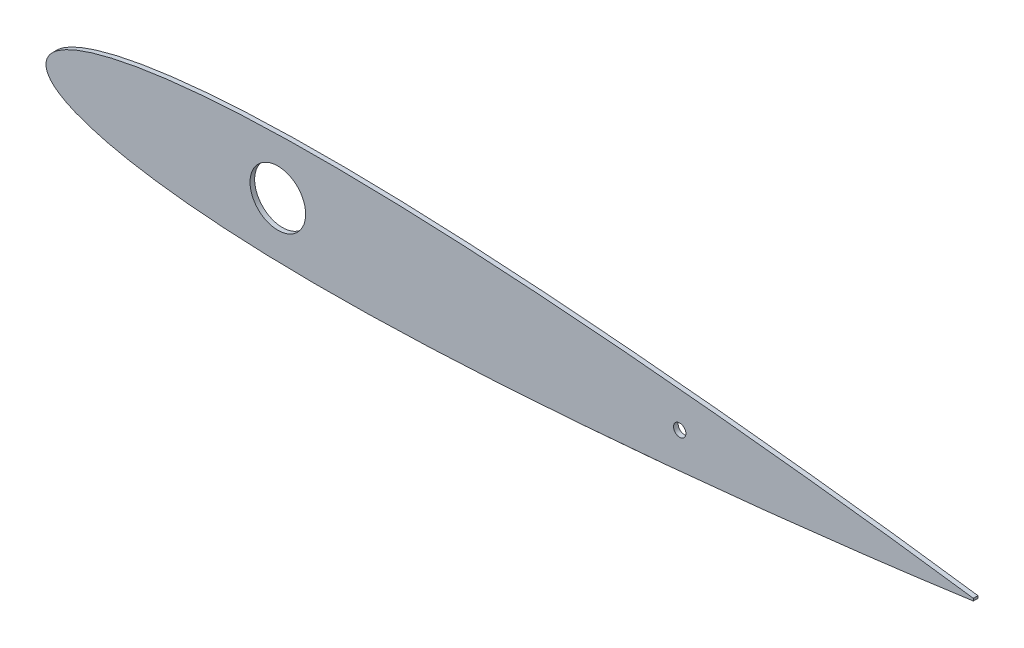
SolidWorks part; units mm, degrees
material "Oak"
ref_plane "Front Plane" through (0, 0, 0) normal (0, 0, 1) x (1, 0, 0)
ref_plane "Top Plane" through (0, 0, 0) normal (0, 1, 0) x (1, 0, 0)
ref_plane "Right Plane" through (0, 0, 0) normal (1, 0, 0) x (0, 0, -1)
sketch "Sketch5" plane through (0, 0, 0) normal (0, 0, 1) x (1, 0, 0)
  line L1 (300, 0.378) -> (300, -0.378)
  spline S1 degree 3 poles (300, 0.378) (299.2704, 0.4794) (297.2347, 0.7625) (293.6597, 1.2577) (289.1124, 1.8742) (284.0808, 2.5445) (278.752, 3.2381) (273.2659, 3.9349) (267.706, 4.629) (262.1146, 5.3131) (256.5083, 5.9822) (250.8917, 6.638) (245.2696, 7.2818) (239.6473, 7.9122) (234.0251, 8.527) (228.3991, 9.1262) (222.7683, 9.7131) (217.1359, 10.2875) (211.5054, 10.8469) (205.8776, 11.3916) (200.2515, 11.9209) (194.6264, 12.4346) (189.0028, 12.9319) (183.3815, 13.4131) (177.7632, 13.8764) (172.1483, 14.3212) (166.5375, 14.7478) (160.9317, 15.1542) (155.3317, 15.5391) (149.7375, 15.9026) (144.1487, 16.2418) (138.5657, 16.5574) (132.9909, 16.8474) (127.4274, 17.1102) (121.8776, 17.3439) (116.3408, 17.5453) (110.8155, 17.7127) (105.3013, 17.8445) (99.8006, 17.9401) (94.3174, 17.9966) (88.8558, 18.0101) (83.4186, 17.9792) (78.0085, 17.8992) (72.6285, 17.767) (67.2827, 17.5794) (61.9774, 17.3315) (56.7207, 17.021) (51.5252, 16.641) (46.4082, 16.1902) (41.3942, 15.6617) (36.5157, 15.054) (31.819, 14.3656) (27.3662, 13.6035) (23.2352, 12.7826) (19.5026, 11.9203) (16.2183, 11.0446) (13.3892, 10.1751) (10.9849, 9.3335) (8.9616, 8.5221) (7.2673, 7.747) (5.8461, 7.0106) (4.6477, 6.3006) (3.6282, 5.6065) (2.7519, 4.9266) (2.0063, 4.2499) (1.3906, 3.5703) (0.901, 2.8909) (0.5293, 2.2202) (0.2605, 1.5665) (0.0857, 0.931) (-0.0035, 0.309) (-0.0035, -0.309) (0.0857, -0.931) (0.2605, -1.5665) (0.5293, -2.2202) (0.901, -2.8909) (1.3906, -3.5703) (2.0063, -4.2499) (2.7519, -4.9266) (3.6282, -5.6065) (4.6477, -6.3006) (5.8461, -7.0106) (7.2673, -7.747) (8.9616, -8.5221) (10.9849, -9.3335) (13.3892, -10.1751) (16.2183, -11.0446) (19.5026, -11.9203) (23.2352, -12.7826) (27.3661, -13.6036) (31.8191, -14.3651) (36.5156, -15.0541) (41.3942, -15.6616) (46.4082, -16.1902) (51.5252, -16.641) (56.7207, -17.021) (61.9774, -17.3315) (67.2827, -17.5794) (72.6285, -17.767) (78.0085, -17.8992) (83.4186, -17.9792) (88.8558, -18.0101) (94.3174, -17.9966) (99.8006, -17.9401) (105.3013, -17.8445) (110.8155, -17.7127) (116.3408, -17.5453) (121.8776, -17.3439) (127.4274, -17.1102) (132.9909, -16.8474) (138.5657, -16.5574) (144.1487, -16.2418) (149.7375, -15.9026) (155.3317, -15.5391) (160.9317, -15.1542) (166.5375, -14.7478) (172.1483, -14.3212) (177.7632, -13.8764) (183.3815, -13.4131) (189.0028, -12.9319) (194.6264, -12.4346) (200.2515, -11.9209) (205.8776, -11.3916) (211.5054, -10.8469) (217.1359, -10.2875) (222.7683, -9.7131) (228.3991, -9.1262) (234.0251, -8.527) (239.6473, -7.9122) (245.2696, -7.2818) (250.8917, -6.638) (256.5083, -5.9822) (262.1146, -5.3131) (267.706, -4.629) (273.2659, -3.9349) (278.752, -3.2381) (284.0808, -2.5445) (289.1124, -1.8742) (293.6597, -1.2577) (297.2347, -0.7625) (299.2704, -0.4794) (300, -0.378) knots 0 0 0 0 0.003612 0.010079 0.017699 0.026115 0.034971 0.04405 0.053234 0.062448 0.071674 0.080921 0.090178 0.099424 0.108664 0.117912 0.12717 0.136427 0.145675 0.154916 0.164153 0.173387 0.182616 0.191838 0.201053 0.21026 0.219459 0.228647 0.237822 0.246985 0.256137 0.265279 0.274407 0.283512 0.292592 0.301646 0.310682 0.319699 0.328695 0.33766 0.346589 0.355477 0.364323 0.373122 0.381868 0.390553 0.399166 0.40769 0.416098 0.424355 0.432412 0.440205 0.447631 0.454564 0.460855 0.466413 0.471229 0.475366 0.478901 0.481915 0.484499 0.486747 0.488741 0.490543 0.492182 0.493673 0.495032 0.496279 0.497425 0.49849 0.499503 0.500497 0.50151 0.502575 0.503721 0.504968 0.506327 0.507818 0.509457 0.511259 0.513253 0.515501 0.518085 0.521099 0.524634 0.528771 0.533587 0.539145 0.545436 0.55237 0.559795 0.567588 0.575645 0.583902 0.59231 0.600834 0.609447 0.618132 0.626878 0.635677 0.644523 0.653411 0.66234 0.671305 0.680301 0.689318 0.698354 0.707408 0.716488 0.725593 0.734721 0.743863 0.753015 0.762178 0.771353 0.780541 0.78974 0.798947 0.808162 0.817384 0.826613 0.835847 0.845084 0.854325 0.863573 0.87283 0.882088 0.891336 0.900576 0.909822 0.919079 0.928326 0.937552 0.946766 0.95595 0.965029 0.973885 0.982301 0.989921 0.996388 1 1 1 1
  dimension "Tail chord" = 300
extrude "Boss-Extrude1" add sketch "Sketch5" along normal blind 1.5
ref_plane "Plane1" through (0, 0, 1.5) normal (0, 0, 1) x (1, 0, 0)
sketch "Sketch7" plane through (0, 0, 1.5) normal (0, 0, 1) x (1, 0, 0)
  circle A0 centre (75, 0) radius 9
  circle A1 centre (205, 0) radius 2
  dimension "D1" = 18
  dimension "D3" = 4
  dimension "Tail chord qtr" = 75
  dimension "Small hole" = 130
extrude "Cut-Extrude7" cut sketch "Sketch7" against normal through all
curve "Curve6"
  spline degree 3 poles (298.242, -0.1932, 0) (300.4407, 0, 0) (298.242, 0.1932, 0) (296.4349, 0.5367, 0) (292.0253, 1.0976, 0) (286.5771, 1.8592, 0) (279.4156, 2.8001, 0) (270.9173, 3.8949, 0) (261.066, 5.1159, 0) (250.0071, 6.4339, 0) (237.8495, 7.8187, 0) (224.7304, 9.2395, 0) (210.7923, 10.6647, 0) (196.1883, 12.0613, 0) (181.0783, 13.3946, 0) (165.6277, 14.6278, 0) (150.0058, 15.7225, 0) (134.3834, 16.6392, 0) (118.9317, 17.3387, 0) (103.8195, 17.7845, 0) (89.2123, 17.9443, 0) (75.2698, 17.7935, 0) (62.1444, 17.3161, 0) (49.9793, 16.5075, 0) (38.907, 15.374, 0) (29.0471, 13.9333, 0) (20.5034, 12.2128, 0) (13.3641, 10.246, 0) (7.6828, 8.0707, 0) (3.4992, 5.7028, 0) (0.7348, 3.1014, 0) (-0.3264, 0, 0) (0.7348, -3.1014, 0) (3.4992, -5.7028, 0) (7.6828, -8.0707, 0) (13.3641, -10.246, 0) (20.5034, -12.2128, 0) (29.0471, -13.9333, 0) (38.907, -15.374, 0) (49.9793, -16.5075, 0) (62.1444, -17.3161, 0) (75.2698, -17.7935, 0) (89.2123, -17.9443, 0) (103.8195, -17.7845, 0) (118.9317, -17.3387, 0) (134.3834, -16.6392, 0) (150.0058, -15.7225, 0) (165.6277, -14.6278, 0) (181.0783, -13.3946, 0) (196.1883, -12.0613, 0) (210.7923, -10.6647, 0) (224.7304, -9.2395, 0) (237.8495, -7.8187, 0) (250.0071, -6.4339, 0) (261.066, -5.1159, 0) (270.9173, -3.8949, 0) (279.4156, -2.8001, 0) (286.5771, -1.8592, 0) (292.0253, -1.0976, 0) (296.4349, -0.5367, 0) (298.242, -0.1932, 0) (300.4407, 0, 0) (298.242, 0.1932, 0) knots -0.012119 -0.005412 -0.001357 0 0.001357 0.005412 0.012119 0.021403 0.033159 0.047255 0.063534 0.081814 0.101892 0.123547 0.146538 0.170613 0.195504 0.220938 0.246636 0.272314 0.297694 0.3225 0.346466 0.36934 0.390884 0.410879 0.429129 0.445462 0.459736 0.471848 0.481751 0.489494 0.495334 0.5 0.504666 0.510506 0.518249 0.528152 0.540264 0.554538 0.570871 0.589121 0.609116 0.63066 0.653534 0.6775 0.702306 0.727686 0.753364 0.779062 0.804496 0.829387 0.853462 0.876453 0.898108 0.918186 0.936466 0.952745 0.966841 0.978597 0.987881 0.994588 0.998643 1 1.001357 1.005412 1.012119 periodic
sketch "Sketch8" plane through (0, 0, 0) normal (0, 0, 1) x (1, 0, 0)
  spline S0 degree 3 poles (298.242, -0.1932) (300.4407, 0) (298.242, 0.1932) (296.4349, 0.5367) (292.0253, 1.0976) (286.5771, 1.8592) (279.4156, 2.8001) (270.9173, 3.8949) (261.066, 5.1159) (250.0071, 6.4339) (237.8495, 7.8187) (224.7304, 9.2395) (210.7923, 10.6647) (196.1883, 12.0613) (181.0783, 13.3946) (165.6277, 14.6278) (150.0058, 15.7225) (134.3834, 16.6392) (118.9317, 17.3387) (103.8195, 17.7845) (89.2123, 17.9443) (75.2698, 17.7935) (62.1444, 17.3161) (49.9793, 16.5075) (38.907, 15.374) (29.0471, 13.9333) (20.5034, 12.2128) (13.3641, 10.246) (7.6828, 8.0707) (3.4992, 5.7028) (0.7348, 3.1014) (-0.3264, 0) (0.7348, -3.1014) (3.4992, -5.7028) (7.6828, -8.0707) (13.3641, -10.246) (20.5034, -12.2128) (29.0471, -13.9333) (38.907, -15.374) (49.9793, -16.5075) (62.1444, -17.3161) (75.2698, -17.7935) (89.2123, -17.9443) (103.8195, -17.7845) (118.9317, -17.3387) (134.3834, -16.6392) (150.0058, -15.7225) (165.6277, -14.6278) (181.0783, -13.3946) (196.1883, -12.0613) (210.7923, -10.6647) (224.7304, -9.2395) (237.8495, -7.8187) (250.0071, -6.4339) (261.066, -5.1159) (270.9173, -3.8949) (279.4156, -2.8001) (286.5771, -1.8592) (292.0253, -1.0976) (296.4349, -0.5367) (298.242, -0.1932) (300.4407, 0) (298.242, 0.1932) knots -0.012119 -0.005412 -0.001357 0 0.001357 0.005412 0.012119 0.021403 0.033159 0.047255 0.063534 0.081814 0.101892 0.123547 0.146538 0.170613 0.195504 0.220938 0.246636 0.272314 0.297694 0.3225 0.346466 0.36934 0.390884 0.410879 0.429129 0.445462 0.459736 0.471848 0.481751 0.489494 0.495334 0.5 0.504666 0.510506 0.518249 0.528152 0.540264 0.554538 0.570871 0.589121 0.609116 0.63066 0.653534 0.6775 0.702306 0.727686 0.753364 0.779062 0.804496 0.829387 0.853462 0.876453 0.898108 0.918186 0.936466 0.952745 0.966841 0.978597 0.987881 0.994588 0.998643 1 1.001357 1.005412 1.012119 only from (300, 0) to (300, 0) construction
  spline S1 degree 3 poles (298.242, -0.1932) (300.4407, 0) (298.242, 0.1932) (296.4349, 0.5367) (292.0253, 1.0976) (286.5771, 1.8592) (279.4156, 2.8001) (270.9173, 3.8949) (261.066, 5.1159) (250.0071, 6.4339) (237.8495, 7.8187) (224.7304, 9.2395) (210.7923, 10.6647) (196.1883, 12.0613) (181.0783, 13.3946) (165.6277, 14.6278) (150.0058, 15.7225) (134.3834, 16.6392) (118.9317, 17.3387) (103.8195, 17.7845) (89.2123, 17.9443) (75.2698, 17.7935) (62.1444, 17.3161) (49.9793, 16.5075) (38.907, 15.374) (29.0471, 13.9333) (20.5034, 12.2128) (13.3641, 10.246) (7.6828, 8.0707) (3.4992, 5.7028) (0.7348, 3.1014) (-0.3264, 0) (0.7348, -3.1014) (3.4992, -5.7028) (7.6828, -8.0707) (13.3641, -10.246) (20.5034, -12.2128) (29.0471, -13.9333) (38.907, -15.374) (49.9793, -16.5075) (62.1444, -17.3161) (75.2698, -17.7935) (89.2123, -17.9443) (103.8195, -17.7845) (118.9317, -17.3387) (134.3834, -16.6392) (150.0058, -15.7225) (165.6277, -14.6278) (181.0783, -13.3946) (196.1883, -12.0613) (210.7923, -10.6647) (224.7304, -9.2395) (237.8495, -7.8187) (250.0071, -6.4339) (261.066, -5.1159) (270.9173, -3.8949) (279.4156, -2.8001) (286.5771, -1.8592) (292.0253, -1.0976) (296.4349, -0.5367) (298.242, -0.1932) (300.4407, 0) (298.242, 0.1932) knots -0.012119 -0.005412 -0.001357 0 0.001357 0.005412 0.012119 0.021403 0.033159 0.047255 0.063534 0.081814 0.101892 0.123547 0.146538 0.170613 0.195504 0.220938 0.246636 0.272314 0.297694 0.3225 0.346466 0.36934 0.390884 0.410879 0.429129 0.445462 0.459736 0.471848 0.481751 0.489494 0.495334 0.5 0.504666 0.510506 0.518249 0.528152 0.540264 0.554538 0.570871 0.589121 0.609116 0.63066 0.653534 0.6775 0.702306 0.727686 0.753364 0.779062 0.804496 0.829387 0.853462 0.876453 0.898108 0.918186 0.936466 0.952745 0.966841 0.978597 0.987881 0.994588 0.998643 1 1.001357 1.005412 1.012119 only from (300, 0) to (300, 0)
equation "\"Tail chord qtr@Sketch7\" = \"Tail chord@Sketch5\" * 0.25"
equation "\"Small hole@Sketch7\" = \"Tail chord qtr@Sketch7\" * 2 - 20"
equation "\"Chord\"= 300mm'Tail chord"
equation "\"Tail chord@Sketch5\"=\"Chord\""
